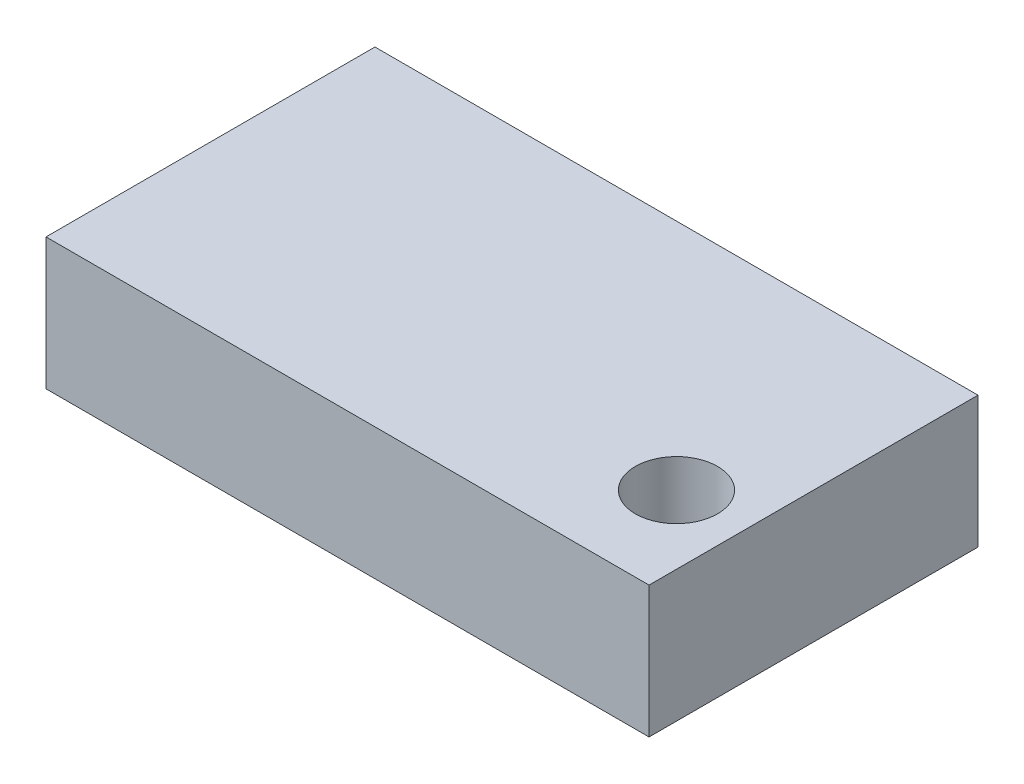
SolidWorks part; units mm, degrees
ref_plane "Front Plane" through (0, 0, 0) normal (0, 0, 1) x (1, 0, 0)
ref_plane "Top Plane" through (0, 0, 0) normal (0, 1, 0) x (1, 0, 0)
ref_plane "Right Plane" through (0, 0, 0) normal (1, 0, 0) x (0, 0, -1)
sketch "Sketch1" plane through (0, 0, 0) normal (0, 1, 0) x (1, 0, 0)
  line L1 (-11, -6) -> (11, -6)
  line L2 (-11, -6) -> (-11, 6)
  line L3 (-11, 6) -> (11, 6)
  line L4 (11, -6) -> (11, 6)
  line L5 (-11, -6) -> (11, 6) construction
  line L6 (-11, 6) -> (11, -6) construction
  circle A0 centre (8.5, -2.5) radius 1.5
  point P0 (0, 0)
  point P10 (8.4722, -6)
  point P11 (8.4443, -6)
  dimension "D3" = 3
  dimension "D4" = 2.5
  dimension "D1" = 22
  dimension "D2" = 12
  dimension "D5" = 3.5
extrude "Boss-Extrude1" add sketch "Sketch1" along normal blind 4.8
